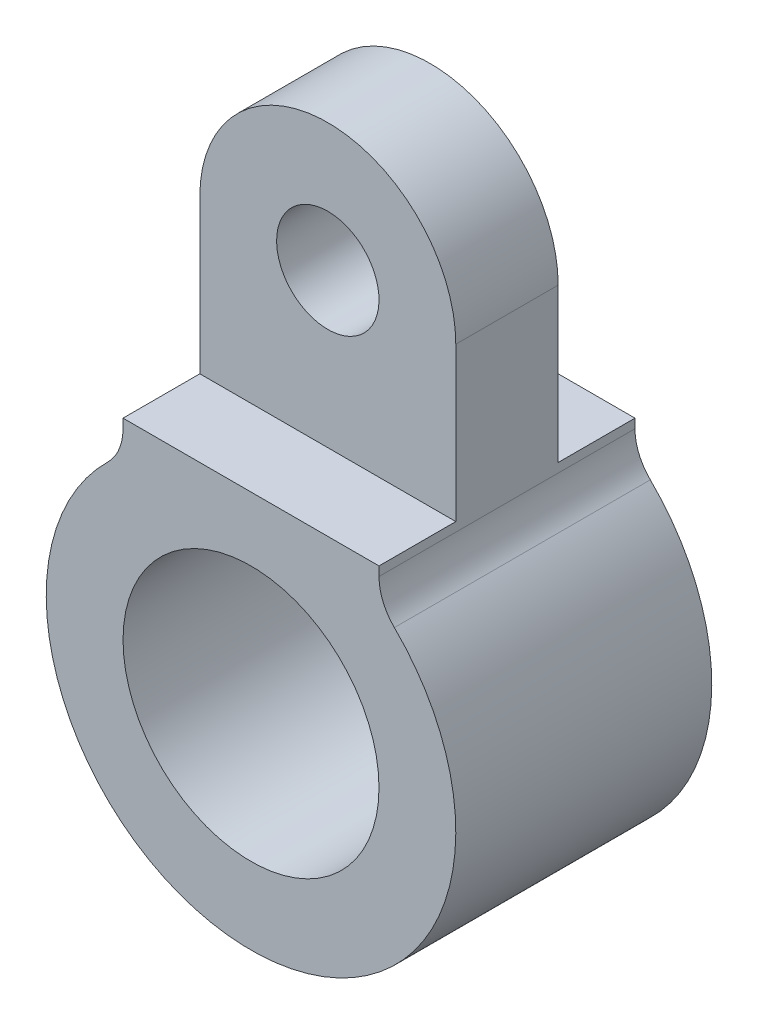
SolidWorks part; units mm, degrees
ref_plane "Plan1" through (0, 0, 0) normal (0, 0, 1) x (1, 0, 0)
ref_plane "Plan2" through (0, 0, 0) normal (0, 1, 0) x (1, 0, 0)
ref_plane "Plan3" through (0, 0, 0) normal (1, 0, 0) x (0, 0, -1)
sketch "Esquisse1" plane through (0, 0, 0) normal (0, 0, 1) x (1, 0, 0)
  line L0 (-20, 0) -> (30, 0) construction
  line L1 (0, 60) -> (0, -20) construction
  line L2 (-10, 27) -> (30, 27) construction
  line L3 (10, 27) -> (10, 12.49)
  line L4 (-10, 27) -> (-10, 12.49)
  arc A0 (-10, 12.49) -> (10, 12.49) centre (0, 0) ccw
  arc A1 (10, 27) -> (-10, 27) centre (0, 27) ccw
  circle A2 centre (0, 0) radius 10
  circle A3 centre (0, 27) radius 4
  dimension "D1" = 16
  dimension "D3" = 10
  dimension "D4" = 20
  dimension "D5" = 8
  dimension "D2" = 27
extrude "Base-Extrusion" add sketch "Esquisse1" along normal blind 20
fillet "Congé1" radius 4 2 edges at (10, 12.49, 10) (-10, 12.49, 10)
sketch "Esquisse4" plane through (0, 0, 0) normal (1, 0, 0) x (0, 0, -1)
  line L0 (-28, 38) -> (-28, 15)
  line L1 (-6, 38) -> (8, 38)
  line L2 (-6, 38) -> (-6, 15)
  line L3 (-10, 33) -> (-10, 16) construction
  line L4 (-6, 15) -> (8, 15)
  line L5 (8, 38) -> (8, 15)
  line L6 (-14, 15) -> (-28, 15)
  line L7 (-14, 38) -> (-14, 15)
  line L8 (-14, 38) -> (-28, 38)
  line L12 (-20, 27) -> (0, 27) construction
  dimension "D1" = 4
  dimension "D3" = 12
  dimension "D4" = 14
extrude "Enlèv. mat.-Extru.4" cut sketch "Esquisse4" against normal mid plane 20
ref_plane "Plan4" through (0, 0, 10) normal (0, 0, -1) x (-1, 0, 0)
